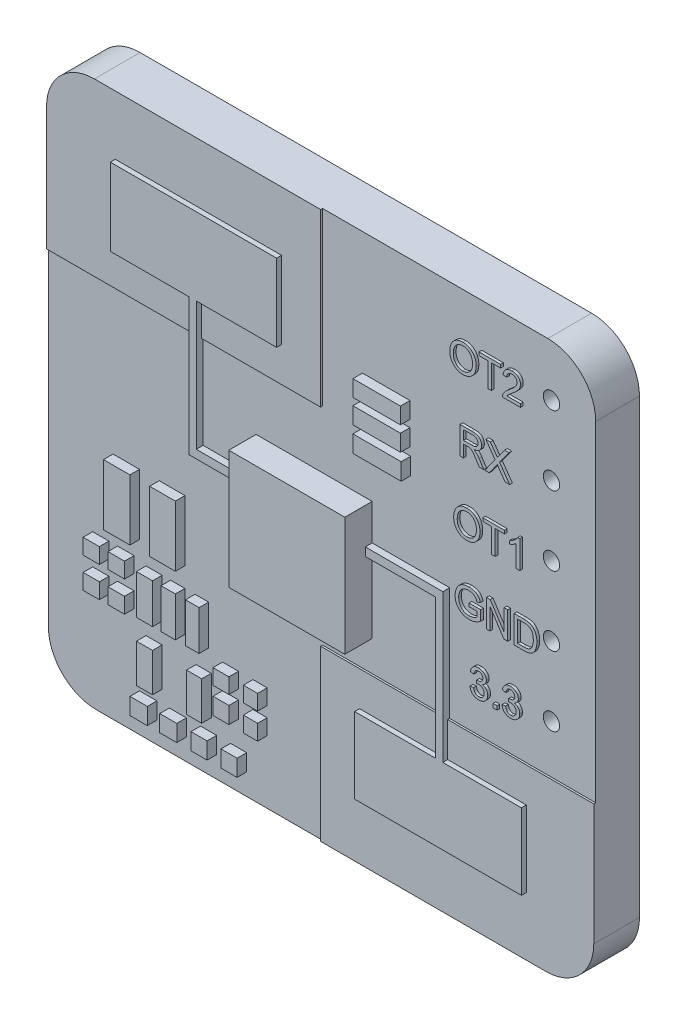
SolidWorks part; units mm, degrees
ref_plane "Plan de face" through (0, 0, 0) normal (0, 0, 1) x (1, 0, 0)
ref_plane "Plan de dessus" through (0, 0, 0) normal (0, 1, 0) x (1, 0, 0)
ref_plane "Plan de droite" through (0, 0, 0) normal (1, 0, 0) x (0, 0, -1)
sketch "pcb" plane through (0, 0, 0) normal (0, 0, 1) x (1, 0, 0)
  line L0 (-88.3794, 37.9422) -> (-68.3794, 37.9422) construction
  line L1 (-78.3986, 44.1613) -> (-91.3146, 44.1613) construction
  line L2 (-88.3829, 37.9329) -> (-88.3829, 45.4975)
  line L4 (-86.6329, 44.1613) -> (-70.1329, 44.1613)
  line L5 (-88.3829, 42.4113) -> (-88.3829, 25.9113)
  line L6 (-86.6329, 24.1613) -> (-70.1329, 24.1613)
  line L7 (-68.3829, 42.4113) -> (-68.3829, 25.9113)
  arc A0 (-70.1329, 44.1613) -> (-68.3829, 42.4113) centre (-70.1329, 42.4113) cw
  arc A1 (-86.6329, 44.1613) -> (-88.3829, 42.4113) centre (-86.6329, 42.4113) ccw
  arc A2 (-70.1329, 24.1613) -> (-68.3829, 25.9113) centre (-70.1329, 25.9113) ccw
  arc A3 (-88.3829, 25.9113) -> (-86.6329, 24.1613) centre (-86.6329, 25.9113) ccw
  circle A4 centre (-69.9993, 42.2724) radius 0.2996
  circle A5 centre (-69.9993, 39.7324) radius 0.2996
  circle A6 centre (-69.9993, 37.1924) radius 0.2996
  circle A7 centre (-69.9993, 34.6524) radius 0.2996
  circle A8 centre (-69.9993, 32.1124) radius 0.2996
  point P12 (-68.3829, 44.1613)
  point P15 (-88.3829, 44.1613)
  point P18 (-68.3829, 24.1613)
  point P21 (-88.3829, 24.1613)
  dimension "D4" = 1.75
  dimension "D1" = 20
  dimension "D2" = 20
  dimension "D3" = 20
  dimension "D5" = 5
sketch "composants" plane through (0, 0, 0) normal (0, 0, 1) x (1, 0, 0)
  line L0 (-82.7276, 39.1741) -> (-79.7936, 39.1741)
  line L1 (-85.8705, 41.9976) -> (-79.7936, 41.9976)
  line L2 (-85.8705, 41.9976) -> (-85.8705, 39.1741)
  line L3 (-85.8705, 39.1741) -> (-82.9897, 39.1741)
  line L4 (-79.7936, 41.9976) -> (-79.7936, 39.1741)
  line L5 (-76.9429, 29.0737) -> (-73.9791, 29.0737)
  line L6 (-76.9429, 29.0737) -> (-76.9429, 26.3015)
  line L7 (-76.9429, 26.3015) -> (-70.8492, 26.3015)
  line L8 (-70.8492, 29.0737) -> (-70.8492, 26.3015)
  line L10 (-73.9791, 29.0737) -> (-73.9791, 34.1766)
  line L11 (-73.9791, 34.4797) -> (-73.7211, 34.4797)
  line L12 (-73.7211, 29.0737) -> (-73.7211, 34.4797)
  line L13 (-73.7211, 34.4797) -> (-82.7276, 34.4797)
  line L14 (-73.7211, 34.4797) -> (-73.7211, 34.1766)
  line L15 (-73.9791, 34.1766) -> (-82.9897, 34.1766)
  line L16 (-82.9897, 34.4797) -> (-82.9897, 34.1766)
  line L17 (-82.9897, 34.1766) -> (-82.7276, 34.1766)
  line L18 (-82.9897, 34.1766) -> (-82.9897, 39.1741)
  line L20 (-82.7276, 34.4797) -> (-82.7276, 39.1741)
  line L21 (-73.7211, 29.0737) -> (-70.8492, 29.0737)
extrude "Boss.-Extru.1" add sketch "composants" along normal blind 0.25 contours L21 L12 L11 L13 L20 L0 L4 L1 L2 L3 L18 L16 L15 L10 L5 L6 L7 L8
sketch "puce" plane through (0, 0, 0) normal (0, 0, 1) x (1, 0, 0)
  line L1 (-80.7922, 35.7946) -> (-76.5526, 35.7946)
  line L2 (-80.7922, 35.7946) -> (-80.7922, 31.4551)
  line L3 (-80.7922, 31.4551) -> (-76.5526, 31.4551)
  line L4 (-76.5526, 35.7946) -> (-76.5526, 31.4551)
extrude "Boss.-Extru.3" add sketch "puce" along normal blind 1
sketch "compos,ates" plane through (0, 0, 0) normal (0, 0, 1) x (1, 0, 0)
  line L1 (-86.0226, 32.558) -> (-85.0545, 32.558)
  line L2 (-86.0226, 32.558) -> (-86.0226, 30.3364)
  line L3 (-86.0226, 30.3364) -> (-85.0545, 30.3364)
  line L4 (-85.0545, 32.558) -> (-85.0545, 30.3364)
  line L5 (-84.3346, 32.558) -> (-83.3945, 32.558)
  line L6 (-84.3346, 32.558) -> (-84.3346, 30.3364)
  line L7 (-84.3346, 30.3364) -> (-83.3945, 30.3364)
  line L8 (-83.3945, 32.558) -> (-83.3945, 30.3364)
  line L9 (-86.7662, 29.7287) -> (-86.1717, 29.7287)
  line L10 (-86.7662, 29.7287) -> (-86.7662, 29.163)
  line L11 (-86.7662, 29.163) -> (-86.1717, 29.163)
  line L12 (-86.1717, 29.7287) -> (-86.1717, 29.163)
  line L13 (-85.8575, 29.7287) -> (-85.2525, 29.7287)
  line L14 (-85.8575, 29.7287) -> (-85.8575, 29.163)
  line L15 (-85.8575, 29.163) -> (-85.2525, 29.163)
  line L16 (-85.2525, 29.7287) -> (-85.2525, 29.163)
  line L17 (-86.7662, 28.6157) -> (-86.1717, 28.6157)
  line L18 (-86.7662, 28.6157) -> (-86.7662, 28.0473)
  line L19 (-86.7662, 28.0473) -> (-86.1717, 28.0473)
  line L20 (-86.1717, 28.6157) -> (-86.1717, 28.0473)
  line L21 (-85.8575, 28.6157) -> (-85.2525, 28.6157)
  line L22 (-85.8575, 28.6157) -> (-85.8575, 28.0473)
  line L23 (-85.8575, 28.0473) -> (-85.2525, 28.0473)
  line L24 (-85.2525, 28.6157) -> (-85.2525, 28.0473)
  line L25 (-82.0184, 27.9759) -> (-81.4369, 27.9759)
  line L26 (-82.0184, 27.9759) -> (-82.0184, 27.4147)
  line L27 (-82.0184, 27.4147) -> (-81.4369, 27.4147)
  line L28 (-81.4369, 27.9759) -> (-81.4369, 27.4147)
  line L29 (-80.9096, 27.9759) -> (-80.3889, 27.9759)
  line L30 (-80.9096, 27.9759) -> (-80.9096, 27.4147)
  line L31 (-80.9096, 27.4147) -> (-80.3889, 27.4147)
  line L32 (-80.3889, 27.9759) -> (-80.3889, 27.4147)
  line L33 (-82.0184, 27.0699) -> (-81.4369, 27.0699)
  line L34 (-82.0184, 27.0699) -> (-82.0184, 26.4614)
  line L35 (-82.0184, 26.4614) -> (-81.4369, 26.4614)
  line L36 (-81.4369, 27.0699) -> (-81.4369, 26.4614)
  line L37 (-80.9096, 27.0293) -> (-80.3889, 27.0293)
  line L38 (-80.9096, 27.0293) -> (-80.9096, 26.4614)
  line L39 (-80.9096, 26.4614) -> (-80.3889, 26.4614)
  line L40 (-80.3889, 27.0293) -> (-80.3889, 26.4614)
  line L41 (-85.0545, 25.5486) -> (-84.4186, 25.5486)
  line L42 (-85.0545, 25.5486) -> (-85.0545, 24.9401)
  line L43 (-85.0545, 24.9401) -> (-84.4186, 24.9401)
  line L44 (-84.4186, 25.5486) -> (-84.4186, 24.9401)
  line L45 (-83.9656, 25.5486) -> (-83.3436, 25.5486)
  line L46 (-83.9656, 25.5486) -> (-83.9656, 24.9401)
  line L47 (-83.9656, 24.9401) -> (-83.3436, 24.9401)
  line L48 (-83.3436, 25.5486) -> (-83.3436, 24.9401)
  line L49 (-82.823, 25.5486) -> (-82.2347, 25.5486)
  line L50 (-82.823, 25.5486) -> (-82.823, 24.9401)
  line L51 (-82.823, 24.9401) -> (-82.2347, 24.9401)
  line L52 (-82.2347, 25.5486) -> (-82.2347, 24.9401)
  line L53 (-81.7277, 25.5486) -> (-81.1394, 25.5486)
  line L54 (-81.7277, 25.5486) -> (-81.7277, 24.9401)
  line L55 (-81.7277, 24.9401) -> (-81.1394, 24.9401)
  line L56 (-81.1394, 25.5486) -> (-81.1394, 24.9401)
  line L57 (-84.8175, 27.4147) -> (-84.2293, 27.4147)
  line L58 (-84.8175, 27.4147) -> (-84.8175, 26.0084)
  line L59 (-84.8175, 26.0084) -> (-84.2293, 26.0084)
  line L60 (-84.2293, 27.4147) -> (-84.2293, 26.0084)
  line L61 (-82.9852, 27.4147) -> (-82.4308, 27.4147)
  line L62 (-82.9852, 27.4147) -> (-82.9852, 26.0084)
  line L63 (-82.9852, 26.0084) -> (-82.4308, 26.0084)
  line L64 (-82.4308, 27.4147) -> (-82.4308, 26.0084)
  line L65 (-84.8175, 29.6188) -> (-84.2293, 29.6188)
  line L66 (-84.8175, 29.6188) -> (-84.8175, 28.1652)
  line L67 (-84.8175, 28.1652) -> (-84.2293, 28.1652)
  line L68 (-84.2293, 29.6188) -> (-84.2293, 28.1652)
  line L69 (-83.9183, 29.6188) -> (-83.3945, 29.6188)
  line L70 (-83.9183, 29.6188) -> (-83.9183, 28.1652)
  line L71 (-83.9183, 28.1652) -> (-83.3945, 28.1652)
  line L72 (-83.3945, 29.6188) -> (-83.3945, 28.1652)
  line L73 (-83.0258, 29.6188) -> (-82.5289, 29.6188)
  line L74 (-83.0258, 29.6188) -> (-83.0258, 28.1652)
  line L75 (-83.0258, 28.1652) -> (-82.5289, 28.1652)
  line L76 (-82.5289, 29.6188) -> (-82.5289, 28.1652)
  line L77 (-76.9066, 39.6785) -> (-75.1684, 39.6785)
  line L78 (-76.9066, 39.6785) -> (-76.9066, 39.0829)
  line L79 (-76.9066, 39.0829) -> (-75.1684, 39.0829)
  line L80 (-75.1684, 39.6785) -> (-75.1684, 39.0829)
  line L81 (-76.9066, 38.8207) -> (-75.1684, 38.8207)
  line L82 (-76.9066, 38.8207) -> (-76.9066, 38.2154)
  line L83 (-76.9066, 38.2154) -> (-75.1684, 38.2154)
  line L84 (-75.1684, 38.8207) -> (-75.1684, 38.2154)
  line L85 (-76.9066, 37.9306) -> (-75.1425, 37.9306)
  line L86 (-76.9066, 37.9306) -> (-76.9066, 37.3123)
  line L87 (-76.9066, 37.3123) -> (-75.1425, 37.3123)
  line L88 (-75.1425, 37.9306) -> (-75.1425, 37.3123)
extrude "Boss.-Extru.4" add sketch "compos,ates" along normal blind 0.35 separate body
sketch "planmasse" plane through (0, 0, 0) normal (0, 0, 1) x (1, 0, 0)
  line L1 (-78.3642, 37.9073) -> (-88.3829, 37.9073)
  line L2 (-78.3642, 37.9073) -> (-78.3642, 44.1613)
  line L3 (-78.3642, 44.1613) -> (-86.6329, 44.1613)
  line L4 (-88.3829, 37.9073) -> (-88.3829, 42.4113)
  line L5 (-78.3642, 30.3412) -> (-68.3829, 30.3412)
  line L6 (-78.3642, 30.3412) -> (-78.3642, 24.1613)
  line L7 (-78.3642, 24.1613) -> (-70.1329, 24.1613)
  line L8 (-68.3829, 30.3412) -> (-68.3829, 25.9113)
  arc A0 (-86.6329, 44.1613) -> (-88.3829, 42.4113) centre (-86.6329, 42.4113) ccw
  arc A1 (-70.1329, 24.1613) -> (-68.3829, 25.9113) centre (-70.1329, 25.9113) ccw
  point P12 (-88.3829, 44.1613)
  point P15 (-68.3829, 24.1613)
  dimension "D1" = 1.75
extrude "Boss.-Extru.5" add sketch "planmasse" along normal blind 0.07
extrude "Boss.-Extru.6" add sketch "pcb" against normal blind 1.6 contours L5 A3 L6 A2 L7 A0 L4 A1 L2 A8 A7 A6 A5 A4
sketch "Esquisse6" plane through (0, 0, 0) normal (0, 0, 1) x (1, 0, 0)
  text T0 "3.3" font "@Arial Unicode MS" height 1
  text T1 "GND" font "@Arial Unicode MS" height 1
  text T2 "OT1" font "@Arial Unicode MS" height 1
  text T3 "RX" font "@Arial Unicode MS" height 1
  text T4 "OT2" font "@Arial Unicode MS" height 1
extrude "Boss.-Extru.7" add sketch "Esquisse6" along normal blind 0.1
